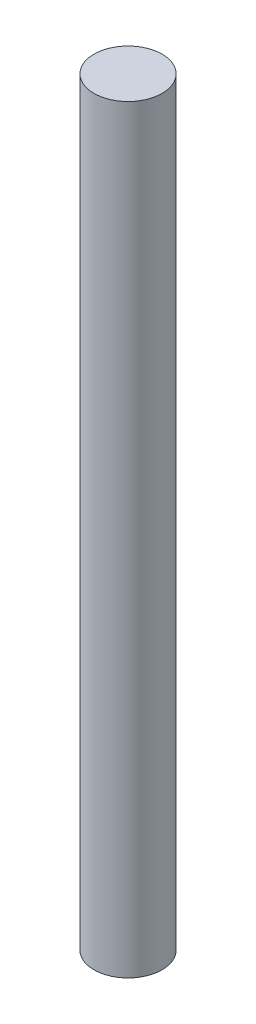
SolidWorks part; units mm, degrees
material "Nylon 101"
ref_plane "Alzado" through (0, 0, 0) normal (0, 0, 1) x (1, 0, 0)
ref_plane "Planta" through (0, 0, 0) normal (0, 1, 0) x (1, 0, 0)
ref_plane "Vista lateral" through (0, 0, 0) normal (1, 0, 0) x (0, 0, -1)
sketch "Sketch1" plane through (0, 0, 0) normal (0, 0, 1) x (1, 0, 0)
  line L0 (0, 0) -> (1.3, 0)
  line L1 (1.3, 0) -> (1.3, -29)
  line L2 (1.3, -29) -> (0, -29)
  line L3 (0, -29) -> (0, 0)
  line L4 (0, -33) -> (0, 4) construction
revolve "Tendon" add sketch "Sketch1" angle 360 about L4
